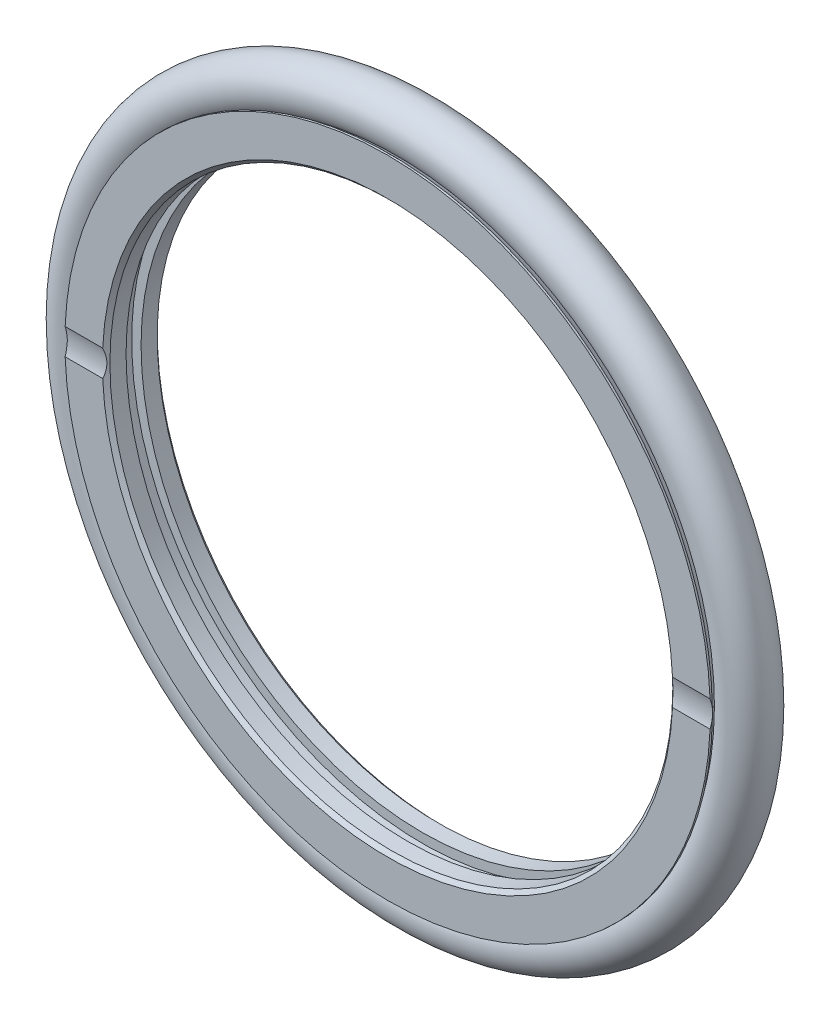
SolidWorks part; units mm, degrees
material "PTFE+FKM"
ref_plane "Front Plane" through (0, 0, 0) normal (0, 0, 1) x (1, 0, 0)
ref_plane "Top Plane" through (0, 0, 0) normal (0, 1, 0) x (1, 0, 0)
ref_plane "Right Plane" through (0, 0, 0) normal (1, 0, 0) x (0, 0, -1)
sketch "Sketch1" plane through (0, 0, 0) normal (1, 0, 0) x (0, 0, -1)
  line L0 (0, 0) -> (7.3636, 0) construction
  line L1 (0, 0) -> (0, 21.4079) construction
  line L2 (-1.35, 17.2) -> (-1.46, 17.2)
  line L3 (-1.46, 17.2) -> (-1.46, 15.2)
  line L4 (-1.26, 15) -> (-0.4, 15)
  line L5 (1.46, 17.2) -> (1.46, 15.2)
  line L6 (1.35, 17.2) -> (1.46, 17.2)
  line L7 (0.4, 15) -> (0.4, 15.5)
  line L8 (0.4, 15.5) -> (-0.4, 15.5)
  line L9 (-0.4, 15) -> (-0.4, 15.5)
  line L10 (0.4, 15) -> (1.26, 15)
  line L11 (-1.46, 15.2) -> (-1.26, 15)
  line L12 (1.46, 15.2) -> (1.26, 15)
  line L13 (-0.5227, 16.825) -> (0.5227, 16.825)
  arc A1 (-1.35, 17.2) -> (-0.5227, 16.825) centre (-0.5227, 17.925) ccw
  arc A2 (1.35, 17.2) -> (0.5227, 16.825) centre (0.5227, 17.925) cw
  point P8 (1.46, 15)
  point P9 (-1.46, 15)
  point P11 (0, 15)
  point P19 (0, 15.5)
  dimension "D3" = 31
  dimension "D5" = 34.4
  dimension "D6" = 0.11
  dimension "D7" = 1.1
  dimension "D10" = 33.65
  dimension "D1" = 2.92
  dimension "D2" = 30
  dimension "D8" = 0.8
revolve "Revolve1" add sketch "Sketch1" angle 360 about L0
sketch "Sketch3" plane through (0, 0, 0) normal (0, 1, 0) x (1, 0, 0)
  line L0 (-0.7, 1.46) -> (0.7, 1.46)
  line L1 (15, 1.46) -> (-15, 1.46) construction
  line L2 (-17.2, -1.46) -> (17.2, -1.46) construction
  arc A0 (-0.7, 1.46) -> (0.7, 1.46) centre (0, 3.4417) ccw
  dimension "D1" = 1.4
  dimension "D2" = 2.8
extrude "Cut-Extrude1" cut sketch "Sketch3" against normal through all and the other way through all
sketch "Sketch4" plane through (0, 0, 0) normal (1, 0, 0) x (0, 0, -1)
  line L0 (-1.46, 0.7) -> (-1.46, -0.7)
  line L1 (-1.46, 17.2) -> (-1.46, -17.2) construction
  line L2 (1.46, -17.1857) -> (1.46, 17.1857) construction
  arc A0 (-1.46, -0.7) -> (-1.46, 0.7) centre (-3.4417, 0) ccw
  dimension "D1" = 1.4
  dimension "D2" = 2.8
extrude "Cut-Extrude2" cut sketch "Sketch4" against normal through all and the other way through all
sketch "Sketch2" plane through (0, 0, 0) normal (1, 0, 0) x (0, 0, -1)
  line L0 (0, 0) -> (10.4197, 0) construction
  circle A0 centre (0, 17.805) radius 1.31
  dimension "D1" = 2.62
  dimension "D2" = 32.99
revolve "Revolve2" add sketch "Sketch2" angle 360 about L0
